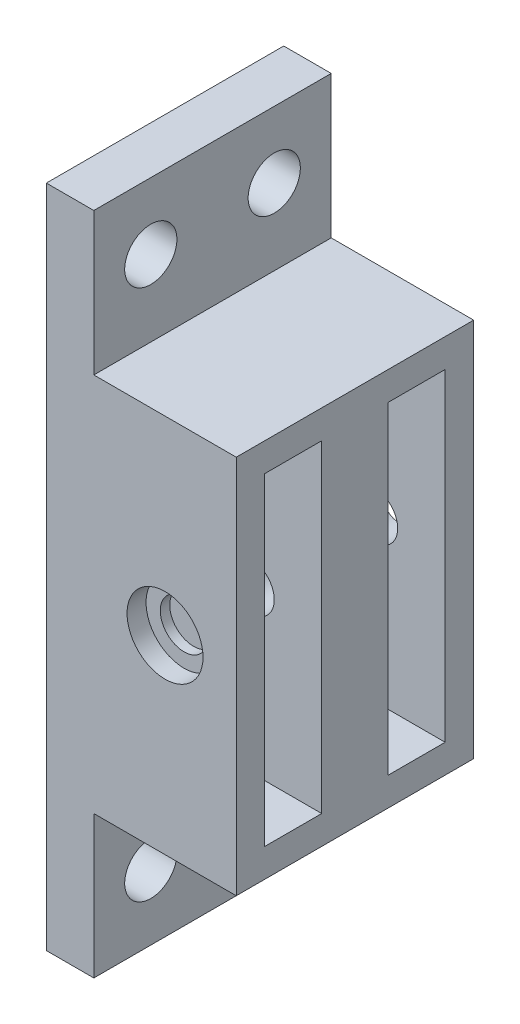
SolidWorks part; units mm, degrees
ref_plane "Přední rovina" through (0, 0, 0) normal (0, 0, 1) x (1, 0, 0)
ref_plane "Horní rovina" through (0, 0, 0) normal (0, 1, 0) x (1, 0, 0)
ref_plane "Pravá rovina" through (0, 0, 0) normal (1, 0, 0) x (0, 0, -1)
sketch "Skica1" plane through (0, 0, 0) normal (1, 0, 0) x (0, 0, -1)
  line L1 (20.32, 51.3888) -> (45.32, 51.3888)
  line L2 (20.32, 51.3888) -> (20.32, -18.6112)
  line L3 (20.32, -18.6112) -> (45.32, -18.6112)
  line L4 (45.32, 51.3888) -> (45.32, -18.6112)
  line L5 (20.32, 51.3888) -> (45.32, -18.6112) construction
  line L6 (20.32, -18.6112) -> (45.32, 51.3888) construction
  circle A0 centre (26.32, 44.3888) radius 2.75
  circle A1 centre (39.32, 44.3888) radius 2.75
  circle A2 centre (26.32, -11.6112) radius 2.75
  circle A3 centre (39.32, -11.6112) radius 2.75
  point P0 (32.82, 16.3888)
  point P14 (0, 0)
  point P15 (32.82, 16.3888)
  dimension "D11" = 5.5
  dimension "D12" = 5.5
  dimension "D13" = 5.5
  dimension "D14" = 5.5
  dimension "D1" = 25
  dimension "D2" = 70
  dimension "D3" = 6
  dimension "D4" = 6
  dimension "D5" = 6
  dimension "D6" = 6
  dimension "D7" = 7
  dimension "D8" = 7
  dimension "D9" = 7
  dimension "D10" = 7
extrude "Přidat vysunutím1" add sketch "Skica1" along normal blind 5
sketch "Skica2" plane through (5, 0, 0) normal (1, 0, 0) x (0, 0, -1)
  line L0 (20.32, 51.3888) -> (20.32, -18.6112) construction
  line L1 (20.32, 36.3888) -> (45.32, 36.3888)
  line L2 (20.32, 36.3888) -> (20.32, -3.6112)
  line L3 (20.32, -3.6112) -> (45.32, -3.6112)
  line L4 (45.32, 36.3888) -> (45.32, -3.6112)
  line L5 (45.32, -18.6112) -> (45.32, 51.3888) construction
  line L6 (45.32, 51.3888) -> (20.32, 51.3888) construction
  line L7 (20.32, -18.6112) -> (45.32, -18.6112) construction
  dimension "D1" = 15
  dimension "D2" = 15
extrude "Přidat vysunutím2" add sketch "Skica2" along normal blind 15
sketch "Skica3" plane through (20, 0, 0) normal (1, 0, 0) x (0, 0, -1)
  line L0 (45.32, 36.3888) -> (20.32, 36.3888) construction
  line L1 (23.32, 33.3888) -> (29.32, 33.3888)
  line L2 (23.32, 33.3888) -> (23.32, -0.6112)
  line L3 (23.32, -0.6112) -> (29.32, -0.6112)
  line L4 (29.32, 33.3888) -> (29.32, -0.6112)
  line L5 (36.32, 33.3888) -> (42.32, 33.3888)
  line L6 (36.32, 33.3888) -> (36.32, -0.6112)
  line L7 (36.32, -0.6112) -> (42.32, -0.6112)
  line L8 (42.32, 33.3888) -> (42.32, -0.6112)
  line L9 (45.32, 36.3888) -> (20.32, 36.3888) construction
  line L10 (20.32, 36.3888) -> (20.32, -3.6112) construction
  line L11 (45.32, -3.6112) -> (45.32, 36.3888) construction
  dimension "D1" = 6
  dimension "D2" = 6
  dimension "D3" = 34
  dimension "D4" = 34
  dimension "D5" = 3
  dimension "D6" = 3
  dimension "D7" = 3
  dimension "D8" = 3
extrude "Odebrat vysunutím1" cut sketch "Skica3" against normal through all
sketch "Skica4" plane through (0, 0, -20.32) normal (0, 0, 1) x (1, 0, 0)
  line L0 (20, 36.3888) -> (5, 36.3888) construction
  line L1 (20, 36.3888) -> (20, -3.6112) construction
  circle A0 centre (12.5, 16.3888) radius 4
  point P4 (0, 0)
  point P6 (32.9719, 5.4211)
  dimension "D1" = 8
  dimension "D2" = 20
  dimension "D3" = 7.5
extrude "Odebrat vysunutím2" cut sketch "Skica4" against normal blind 2
sketch "Skica5" plane through (0, 0, -22.32) normal (0, 0, 1) x (1, 0, 0)
  circle A0 centre (12.5, 16.3888) radius 2.5
  dimension "D1" = 5
extrude "Odebrat vysunutím3" cut sketch "Skica5" against normal through all
